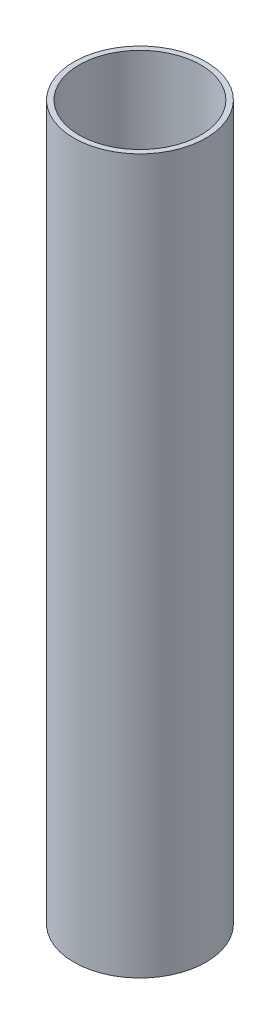
SolidWorks part; units mm, degrees
material "3.1355 (EN-AW 2024)"
ref_plane "Спереди" through (0, 0, 0) normal (0, 0, 1) x (1, 0, 0)
ref_plane "Сверху" through (0, 0, 0) normal (0, 1, 0) x (1, 0, 0)
ref_plane "Справа" through (0, 0, 0) normal (1, 0, 0) x (0, 0, -1)
sketch "Эскиз1" plane through (0, 0, 0) normal (0, 1, 0) x (1, 0, 0)
  circle A0 centre (0, 0) radius 12.5
  circle A1 centre (0, 0) radius 11.5
  dimension "D1" = 25
  dimension "D2" = 23
extrude "Бобышка-Вытянуть1" add sketch "Эскиз1" along normal blind 135
equation "\"D2@Эскиз1\"=\"D1@Эскиз1\"-2"
